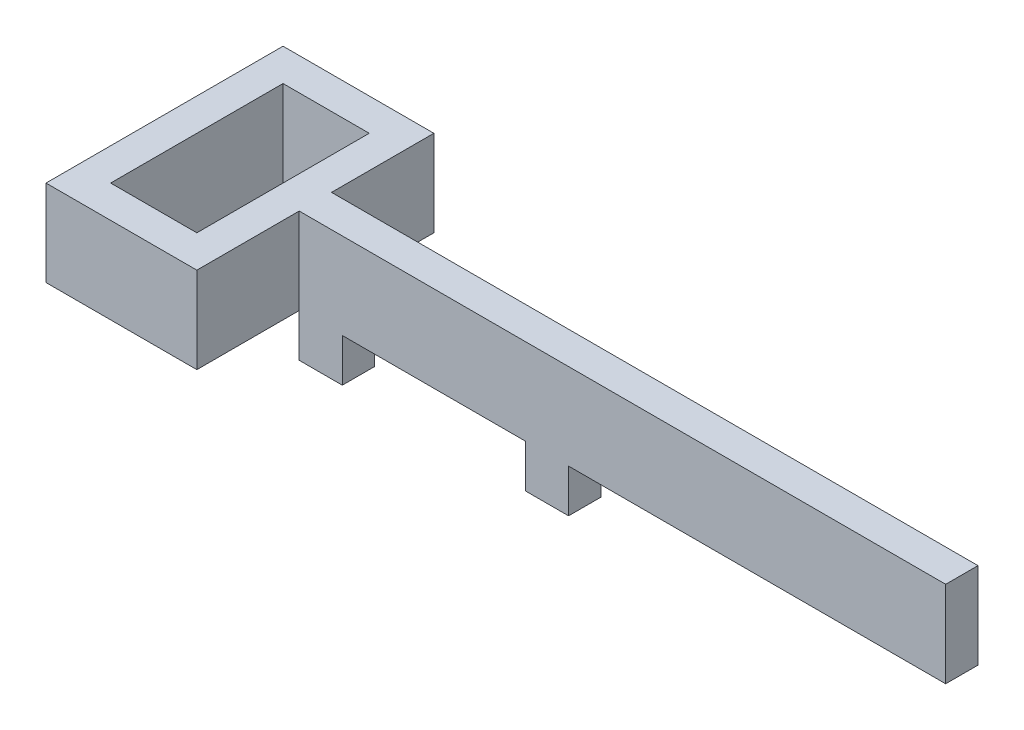
SolidWorks part; units mm, degrees
ref_plane "Front Plane" through (0, 0, 0) normal (0, 0, 1) x (1, 0, 0)
ref_plane "Top Plane" through (0, 0, 0) normal (0, 1, 0) x (1, 0, 0)
ref_plane "Right Plane" through (0, 0, 0) normal (1, 0, 0) x (0, 0, -1)
sketch "Sketch1" plane through (0, 0, 0) normal (0, 1, 0) x (1, 0, 0)
  line L1 (-3.5, -5.5) -> (3.5, -5.5)
  line L2 (-3.5, -5.5) -> (-3.5, 5.5)
  line L3 (-3.5, 5.5) -> (3.5, 5.5)
  line L4 (3.5, -5.5) -> (3.5, 5.5)
  line L5 (-3.5, -5.5) -> (3.5, 5.5) construction
  line L6 (-3.5, 5.5) -> (3.5, -5.5) construction
  line L7 (-2, -4) -> (2, -4)
  line L8 (-2, -4) -> (-2, 4)
  line L9 (-2, 4) -> (2, 4)
  line L10 (2, -4) -> (2, 4)
  line L11 (-2, -4) -> (2, 4) construction
  line L12 (-2, 4) -> (2, -4) construction
  line L17 (3.5, 0.75) -> (33.5, 0.75)
  line L18 (3.5, 0.75) -> (3.5, -0.75)
  line L19 (3.5, -0.75) -> (33.5, -0.75)
  line L20 (33.5, 0.75) -> (33.5, -0.75)
  point P0 (0, 0)
  point P7 (0, 0)
  point P15 (3.5, 0)
  point P16 (3.5, 0)
  dimension "D1" = 8
  dimension "D2" = 4
  dimension "D3" = 1.5
  dimension "D4" = 1.5
  dimension "D5" = 1.5
  dimension "D6" = 30
extrude "Boss-Extrude1" add sketch "Sketch1" along normal blind 4 contours L20 L17 L4 L19 | L1 L4 L3 L2 L10 L7 L8 L9
sketch "Sketch2" plane through (0, 0, 0) normal (0, -1, 0) x (1, 0, 0)
  line L0 (3.5, 0.75) -> (33.5, 0.75) construction
  line L1 (14, 0.75) -> (16, 0.75)
  line L2 (14, 0.75) -> (14, -0.75)
  line L3 (14, -0.75) -> (16, -0.75)
  line L4 (16, 0.75) -> (16, -0.75)
  line L5 (3.5, -0.75) -> (33.5, -0.75) construction
  line L6 (-2, 4) -> (-2, -4) construction
  dimension "D1" = 2
  dimension "D2" = 18
extrude "Boss-Extrude2" add sketch "Sketch2" along normal blind 2
sketch "Sketch3" plane through (0, 0, 0) normal (0, -1, 0) x (-1, 0, 0)
  line L0 (-3.5, 0.75) -> (-14, 0.75) construction
  line L1 (-3.5, -0.75) -> (-5.5, -0.75)
  line L2 (-3.5, -0.75) -> (-3.5, 0.75)
  line L3 (-3.5, 0.75) -> (-5.5, 0.75)
  line L4 (-5.5, -0.75) -> (-5.5, 0.75)
  dimension "D1" = 2
extrude "Boss-Extrude3" add sketch "Sketch3" along normal blind 2
